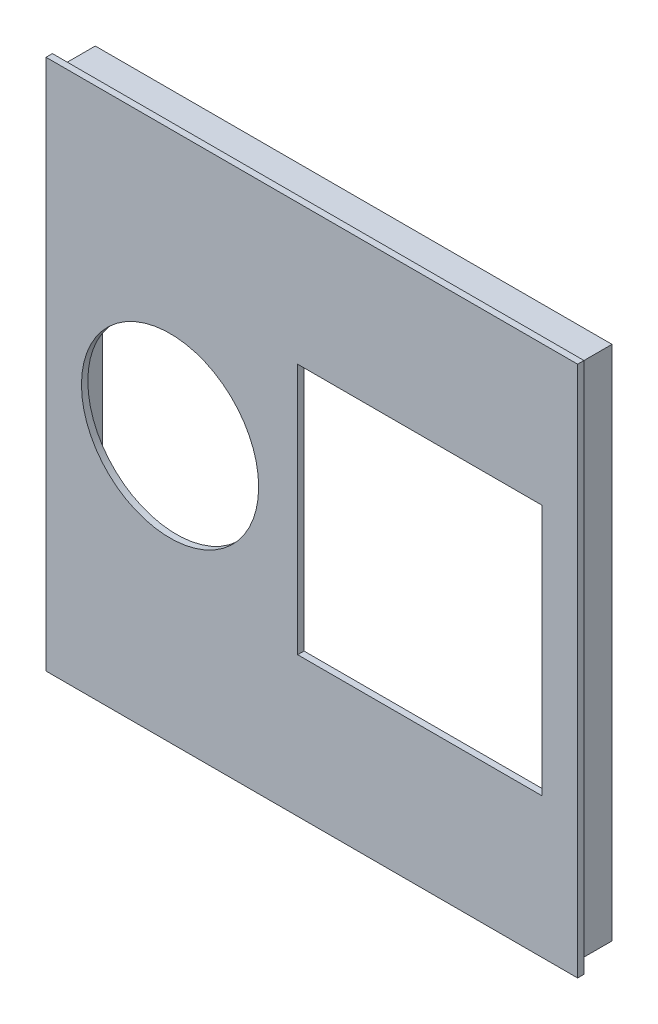
SolidWorks part; units mm, degrees
ref_plane "Alzado" through (0, 0, 0) normal (0, 0, 1) x (1, 0, 0)
ref_plane "Planta" through (0, 0, 0) normal (0, 1, 0) x (1, 0, 0)
ref_plane "Vista lateral" through (0, 0, 0) normal (1, 0, 0) x (0, 0, -1)
sketch "Croquis1" plane through (0, 0, 0) normal (0, 0, 1) x (1, 0, 0)
  line L0 (-17.4247, -67.5529) -> (132.5753, -67.5529) construction
  line L1 (-17.4247, 7.4471) -> (132.5753, 7.4471)
  line L2 (-17.4247, 7.4471) -> (-17.4247, -142.5529)
  line L3 (-17.4247, -142.5529) -> (132.5753, -142.5529)
  line L4 (132.5753, 7.4471) -> (132.5753, -142.5529)
  line L6 (53.5753, -32.0529) -> (122.5753, -32.0529)
  line L7 (53.5753, -32.0529) -> (53.5753, -103.0529)
  line L8 (53.5753, -103.0529) -> (122.5753, -103.0529)
  line L9 (122.5753, -32.0529) -> (122.5753, -103.0529)
  circle A0 centre (17.5753, -67.5529) radius 25
  dimension "D7" = 36
  dimension "D8" = 50
  dimension "D1" = 150
  dimension "D2" = 150
  dimension "D3" = 10
  dimension "D4" = 69
  dimension "D5" = 71
  dimension "D6" = 35.5
extrude "Saliente-Extruir1" add sketch "Croquis1" along normal blind 1.8
sketch "Croquis2" plane through (0, 0, 0) normal (0, 0, -1) x (-1, 0, 0)
  line L0 (17.4247, -142.5529) -> (-132.5753, -142.5529) construction
  line L1 (15.3247, -140.4529) -> (-130.4753, -140.4529)
  line L2 (15.3247, -140.4529) -> (15.3247, 5.3471)
  line L3 (15.3247, 5.3471) -> (-130.4753, 5.3471)
  line L4 (-130.4753, -140.4529) -> (-130.4753, 5.3471)
  line L5 (-132.5753, -142.5529) -> (-132.5753, 7.4471) construction
  line L6 (17.4247, 7.4471) -> (17.4247, -142.5529) construction
  line L7 (-132.5753, 7.4471) -> (17.4247, 7.4471) construction
  line L9 (13.2247, -138.3529) -> (-128.3753, -138.3529)
  line L10 (13.2247, -138.3529) -> (13.2247, 3.2471)
  line L11 (13.2247, 3.2471) -> (-128.3753, 3.2471)
  line L12 (-128.3753, -138.3529) -> (-128.3753, 3.2471)
  dimension "D1" = 2.1
  dimension "D2" = 2.1
  dimension "D3" = 2.1
  dimension "D4" = 2.1
  dimension "D5" = 2.1
  dimension "D6" = 2.1
  dimension "D7" = 2.1
  dimension "D8" = 2.1
extrude "Saliente-Extruir2" add sketch "Croquis2" along normal blind 10
